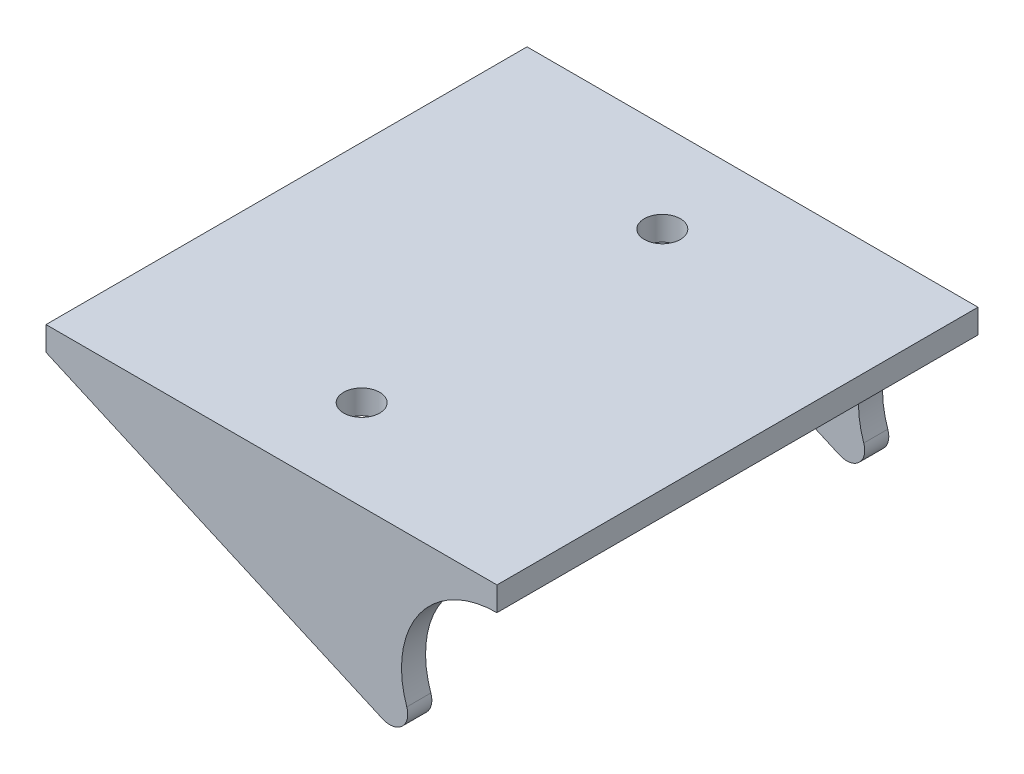
SolidWorks part; units mm, degrees
ref_plane "Front Plane" through (0, 0, 0) normal (0, 0, 1) x (1, 0, 0)
ref_plane "Top Plane" through (0, 0, 0) normal (0, 1, 0) x (1, 0, 0)
ref_plane "Right Plane" through (0, 0, 0) normal (1, 0, 0) x (0, 0, -1)
sketch "Sketch1" plane through (0, 0, 0) normal (0, 0, 1) x (1, 0, 0)
  line L0 (0, 15.875) -> (0, 19.875)
  line L1 (0, 19.875) -> (-75, 19.875)
  line L2 (-75, 19.875) -> (-75, 15.875)
  line L3 (-75, 15.875) -> (-6.4322, -14.5135)
  arc A0 (0, 15.875) -> (-6.4322, -14.5135) centre (0, 0) ccw
  point P1 (0, 0)
  point P5 (0, 0)
  point P9 (0, 0)
  point P10 (0, 0)
  point P11 (0, 0)
  point P12 (-8.3332, -13.512)
  dimension "D1" = 31.75
  dimension "D2" = 4
  dimension "D3" = 4
  dimension "D4" = 75
extrude "Boss-Extrude1" add sketch "Sketch1" along normal blind 4
sketch "Sketch2" plane through (0, 0, 4) normal (0, 0, 1) x (1, 0, 0)
  line L0 (0, 15.875) -> (-75, 15.875)
  line L1 (-75, 15.875) -> (-75, 19.875)
  line L2 (-75, 19.875) -> (0, 19.875)
  line L3 (0, 19.875) -> (0, 15.875)
extrude "Boss-Extrude2" add sketch "Sketch2" along normal blind 72
sketch "Sketch4" plane through (0, 0, 76) normal (0, 0, 1) x (1, 0, 0)
  line L0 (-75, 19.875) -> (-75, 15.875)
  line L1 (-75, 15.875) -> (-6.4322, -14.5135)
  line L2 (-75, 19.875) -> (0, 19.875)
  line L3 (0, 19.875) -> (0, 15.875)
  arc A0 (-6.4322, -14.5135) -> (0, 15.875) centre (0, 0) cw
  dimension "D1" = 15.875
extrude "Boss-Extrude3" add sketch "Sketch4" along normal blind 4
sketch "Sketch5" plane through (0, 19.875, 0) normal (0, 1, 0) x (1, 0, 0)
  line L1 (-37.5, -15) -> (-37.5, -65) construction
  line L2 (0, 0) -> (-75, -80) construction
  circle A0 centre (-37.5, -15) radius 3
  circle A1 centre (-37.5, -65) radius 3
  point P6 (-37.5, -40)
  dimension "D2" = 6
  dimension "D3" = 6
  dimension "D1" = 50
extrude "Cut-Extrude1" cut sketch "Sketch5" against normal blind 4
fillet "Fillet1" radius 3 2 edges at (-6.4322, -14.5135, 78) (-6.4322, -14.5135, 2)
